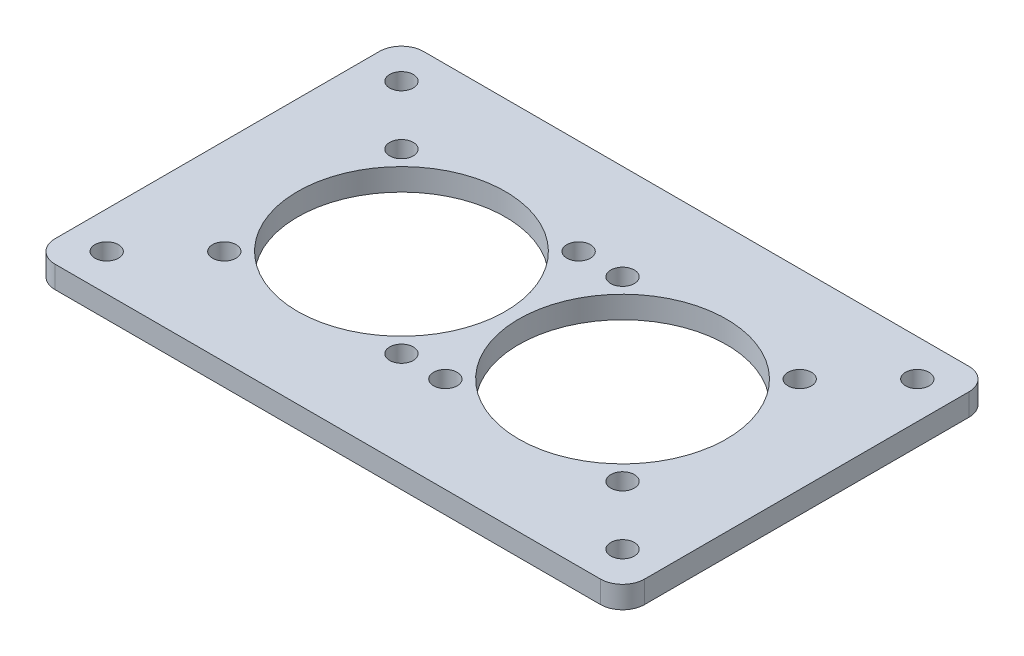
SolidWorks part; units mm, degrees
material "橡木"
ref_plane "Front" through (0, 0, 0) normal (0, 0, 1) x (1, 0, 0)
ref_plane "Top" through (0, 0, 0) normal (0, 1, 0) x (1, 0, 0)
ref_plane "Right" through (0, 0, 0) normal (1, 0, 0) x (0, 0, -1)
sketch "草图1" plane through (0, 0, 0) normal (0, 0, 1) x (1, 0, 0)
  line L1 (-30, -15) -> (30, -15)
  line L2 (-30, -15) -> (-30, 15)
  line L3 (-30, 15) -> (30, 15)
  line L4 (30, -15) -> (30, 15)
  line L5 (0, 15) -> (0, -15) construction
  line L6 (-30, 0) -> (30, 0) construction
  point P0 (0, 0)
  dimension "D1" = 60
  dimension "D2" = 30
extrude "凸台-拉伸1" add sketch "草图1" along normal blind 30
sketch "草图2" plane through (0, -15, 0) normal (0, -1, 0) x (1, 0, 0)
  line L4 (-30, 0) -> (30, 0)
  line L5 (30, 0) -> (30, 30)
  line L6 (30, 30) -> (-30, 30)
  line L7 (-30, 30) -> (-30, 0)
  line L8 (-30, 0) -> (30, 0)
  line L9 (30, 0) -> (30, 30)
  line L10 (30, 30) -> (-30, 30)
  line L11 (-30, 30) -> (-30, 0)
  dimension "D1" = 0
extrude "切除-拉伸1" cut sketch "草图2" against normal blind 27
sketch "草图3" plane through (0, 15, 0) normal (0, 1, 0) x (1, 0, 0)
  line L0 (-30, -30) -> (0, 0) construction
  line L1 (0, 0) -> (30, -30) construction
  line L2 (-30, 0) -> (0, -30) construction
  line L3 (30, -30) -> (-30, -30) construction
  line L4 (0, -30) -> (30, 0) construction
  line L5 (0, 0) -> (0, -30) construction
  line L6 (-27.0208, -27.0208) -> (-2.9792, -27.0208) construction
  line L7 (-27.0208, -27.0208) -> (-27.0208, -2.9792) construction
  line L8 (-27.0208, -2.9792) -> (-2.9792, -2.9792) construction
  line L9 (-2.9792, -27.0208) -> (-2.9792, -2.9792) construction
  line L10 (-15, -2.9792) -> (-15, -27.0208) construction
  line L11 (-27.0208, -15) -> (-2.9792, -15) construction
  circle A0 centre (-27.0208, -2.9792) radius 1.6
  circle A1 centre (-2.9792, -2.9792) radius 1.6
  circle A2 centre (-2.9792, -27.0208) radius 1.6
  circle A3 centre (-27.0208, -27.0208) radius 1.6
  circle A4 centre (27.0208, -27.0208) radius 1.6
  circle A5 centre (2.9792, -27.0208) radius 1.6
  circle A6 centre (2.9792, -2.9792) radius 1.6
  circle A7 centre (27.0208, -2.9792) radius 1.6
  circle A8 centre (-15, -15) radius 14.1
  circle A9 centre (15, -15) radius 14.1
  point P11 (-15, -15)
  dimension "D1" = 3.2
  dimension "D3" = 28.2
  dimension "D2" = 34
extrude "切除-拉伸2" cut sketch "草图3" against normal through all
sketch "草图4" plane through (0, 15, 0) normal (0, 1, 0) x (1, 0, 0)
  line L0 (30, -30) -> (-30, -30) construction
  line L1 (30, -30) -> (30, 0) construction
  line L2 (30, 0) -> (-30, 0) construction
  line L3 (-30, -30) -> (-30, 0) construction
  line L4 (30, -30) -> (-30, -30)
  line L5 (30, -30) -> (30, 0)
  line L6 (30, 0) -> (-30, 0)
  line L7 (-30, -30) -> (-30, 0)
  line L8 (40, -40) -> (-40, -40)
  line L9 (-40, -40) -> (-40, 10)
  line L10 (40, 10) -> (-40, 10)
  line L11 (40, -40) -> (40, 10)
  dimension "D1" = 10
extrude "凸台-拉伸2" add sketch "草图4" against normal blind 3
sketch "草图5" plane through (0, 15, 0) normal (0, 1, 0) x (1, 0, 0)
  line L0 (40, 10) -> (-40, 10) construction
  line L1 (-35, -35) -> (35, -35) construction
  line L2 (-35, -35) -> (-35, 5) construction
  line L3 (-35, 5) -> (35, 5) construction
  line L4 (35, -35) -> (35, 5) construction
  line L5 (0, 5) -> (0, -35) construction
  line L6 (-35, -15) -> (35, -15) construction
  line L7 (40, -40) -> (40, 10) construction
  circle A0 centre (-35, 5) radius 1.6
  circle A1 centre (35, 5) radius 1.6
  circle A2 centre (35, -35) radius 1.6
  circle A3 centre (-35, -35) radius 1.6
  point P0 (0, -15)
  point P7 (0, 10)
  point P14 (40, -15)
  dimension "D3" = 3.2
  dimension "D1" = 40
  dimension "D2" = 70
extrude "切除-拉伸3" cut sketch "草图5" against normal blind 3
fillet "圆角1" radius 3 4 edges at (40, 13.5, -10) (-40, 13.5, 40) (40, 13.5, 40) (-40, 13.5, -10)
